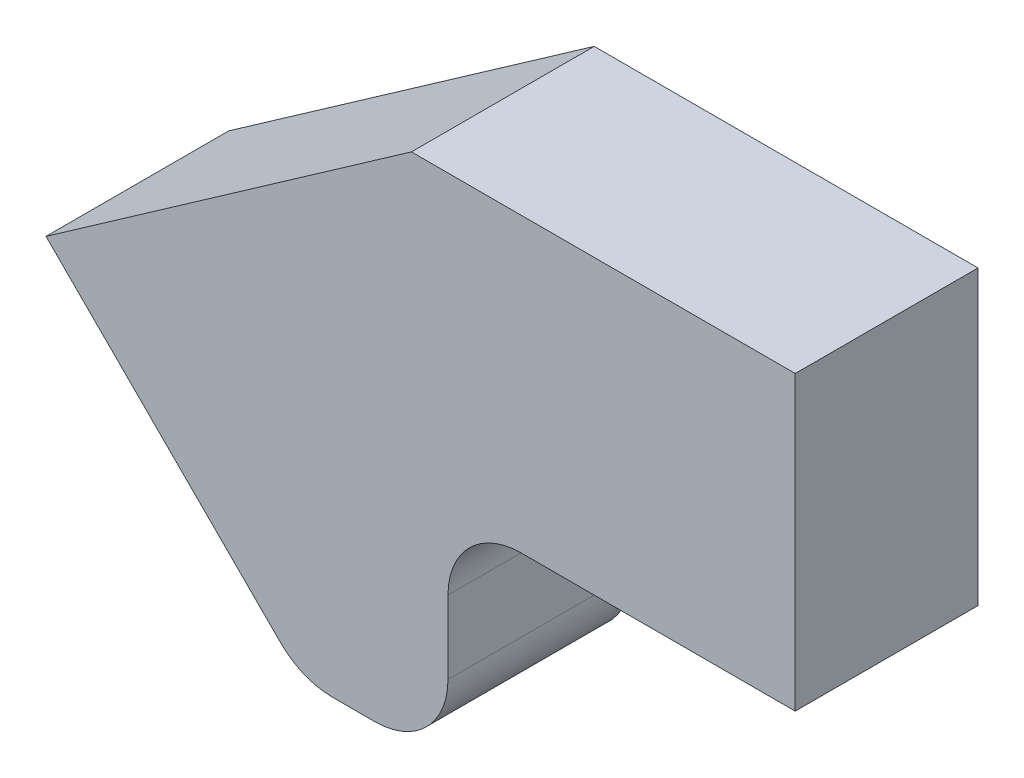
SolidWorks part; units mm, degrees
material "PBT General Purpose"
ref_plane "Front Plane" through (0, 0, 0) normal (0, 0, 1) x (1, 0, 0)
ref_plane "Top Plane" through (0, 0, 0) normal (0, 1, 0) x (1, 0, 0)
ref_plane "Right Plane" through (0, 0, 0) normal (1, 0, 0) x (0, 0, -1)
sketch "frame_outline" plane through (0, 0, 0) normal (0, 0, 1) x (1, 0, 0)
  line L80 (0, 0) -> (0.4999, 0.35)
  line L83 (0.4999, 0.35) -> (1.0249, 0.35)
  line L84 (1.0249, 0.35) -> (1.0249, -0.05)
  line L85 (1.0249, -0.05) -> (0.5499, -0.05)
  line L86 (0.5499, -0.05) -> (0.5499, -0.35)
  line L87 (0.5499, -0.35) -> (0.35, -0.35)
  line L88 (0.35, -0.35) -> (0, 0)
  line L89 (0, 0) -> (0.55, 0) construction
  dimension "D18" = 0.4
  dimension "D20" = 0.3
  dimension "D23" = 35
  dimension "D21" = 0.525
  dimension "D22" = 45
  dimension "D3" = 0.475
  dimension "D4" = 0.05
  dimension "D5" = 0.6102
extrude "Boss-Extrude1" add sketch "frame_outline" along normal mid plane 0.25
fillet "Fillet1" radius 0.1 3 edges at (0.5499, -0.35, 0) (0.5499, -0.05, 0) (0.35, -0.35, 0)
equation "\"t\"= 0.25'thickness of the sheets"
equation "\"t_cf\" = 0.115'thickness of single carbon fiber layer"
equation "\"t_kapton\" = 0.025'thickness of single Kapton flex layer"
equation "\"t_fr4\" = 0.1'thickness of FR4 with copper layer"
equation "\"joint_flex\"= 0.1'Width of flextures gap"
equation "\"joint_flex_eff\"= 0.02'Width of flecture after castelation"
equation "\"joint_fold\"= 0.2'Width of folding joints for 90deg fold"
equation "\"gap_tolerance\"= 0.002'Width to have interfecence fit between carbon fiber inserts"
equation "\"assemble_angle\"= 90'Angle of assembly parts"
equation "\"D1@Boss-Extrude1\"=\"t\""
equation "\"link_lift\"= 0.5'Actuation linkage amplification for the lift motion"
equation "\"link_swing\"= 0.45'Actuation linkage amplification for the swing motion"
equation "\"D21@frame_outline\"=1.05 + \"joint_flex\"/2 -\"link_swing\"-\"t\"/2"
equation "\"D3@frame_outline\"=\"t\"*2.5-\"joint_fold\"+0.05"
